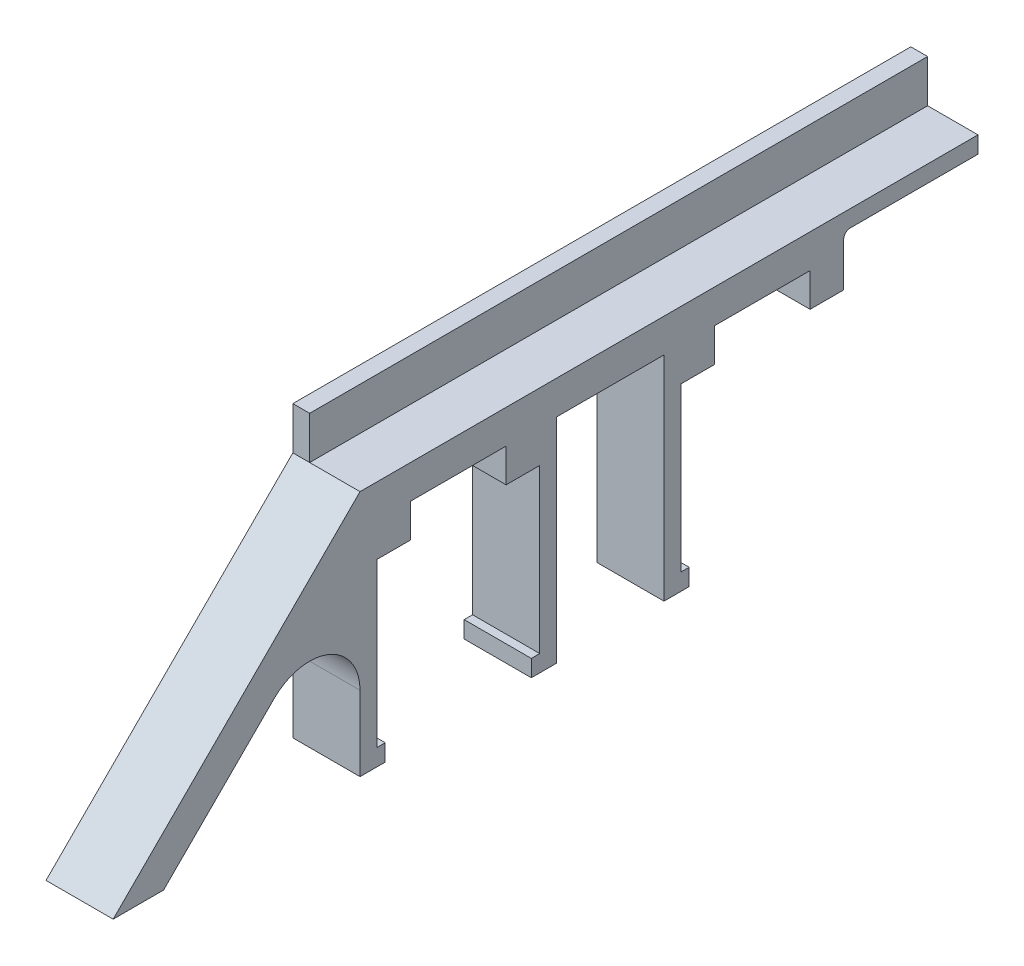
SolidWorks part; units mm, degrees
ref_plane "Front" through (0, 0, 0) normal (0, 0, 1) x (1, 0, 0)
ref_plane "Top" through (0, 0, 0) normal (0, 1, 0) x (1, 0, 0)
ref_plane "Right" through (0, 0, 0) normal (1, 0, 0) x (0, 0, -1)
sketch "Sketch1" plane through (0, 0, 0) normal (1, 0, 0) x (0, 0, -1)
  line L16 (-5, 68.5) -> (-5, -5)
  line L17 (-5, -5) -> (2.5, -5)
  line L18 (2.5, -5) -> (2.5, 0)
  line L19 (2.5, 0) -> (0, 0)
  line L20 (0, 0) -> (0, 48.5)
  line L21 (0, 48.5) -> (10, 48.5)
  line L22 (10, 48.5) -> (10, 58.5)
  line L23 (10, 58.5) -> (38.5, 58.5)
  line L24 (38.5, 58.5) -> (38.5, 48.5)
  line L25 (38.5, 48.5) -> (48.5, 48.5)
  line L26 (48.5, 48.5) -> (48.5, 0)
  line L27 (48.5, 0) -> (53.5, 0)
  line L28 (53.5, 0) -> (53.5, 58.5)
  line L29 (53.5, 58.5) -> (85.5, 58.5)
  line L30 (69.5, 58.5) -> (69.5, 90.1855)
  line L31 (-5, 68.5) -> (144, 68.5)
  line L32 (85.5, 0) -> (85.5, 58.5)
  line L33 (90.5, 0) -> (85.5, 0)
  line L34 (90.5, 48.5) -> (90.5, 0)
  line L35 (100.5, 48.5) -> (90.5, 48.5)
  line L36 (100.5, 58.5) -> (100.5, 48.5)
  line L37 (129, 58.5) -> (100.5, 58.5)
  line L38 (129, 48.5) -> (129, 58.5)
  line L39 (139, 48.5) -> (129, 48.5)
  line L40 (139, 0) -> (139, 48.5)
  line L41 (136.5, 0) -> (139, 0)
  line L42 (136.5, -5) -> (136.5, 0)
  line L43 (144, -5) -> (136.5, -5)
  line L44 (144, 68.5) -> (144, -5)
  line L45 (48.5, 0) -> (46, 0)
  line L46 (46, 0) -> (46, -5)
  line L47 (53.5, 0) -> (53.5, -5)
  line L48 (53.5, -5) -> (46, -5)
  line L49 (85.5, 0) -> (85.5, -5)
  line L50 (85.5, -5) -> (93, -5)
  line L51 (93, 0) -> (93, -5)
  line L52 (90.5, 0) -> (93, 0)
  line L53 (90.5, 0) -> (85.5, 0)
  line L54 (139, 48.5) -> (139, 68.5)
  line L55 (-5, 68.5) -> (-78.5, -5)
  line L56 (-5, -5) -> (-78.5, -5)
  line L57 (-78.5, -5) -> (-63.5, -5)
  line L58 (-63.5, -5) -> (-5, 53.5)
  line L59 (139, 63.5) -> (179, 63.5)
  line L60 (179, 63.5) -> (179, 68.5)
  line L61 (179, 68.5) -> (144, 68.5)
  point P9 (51, 0)
  point P32 (69.5, 68.5)
  dimension "D1" = 20
  dimension "D2" = 20
  dimension "D3" = 2.5
  dimension "D4" = 5
  dimension "D5" = 48.5
  dimension "D6" = 42
  dimension "D7" = 10
  dimension "D8" = 10
  dimension "D9" = 5
  dimension "D10" = 48.5
  dimension "D11" = 48.5
  dimension "D12" = 5
  dimension "D13" = 5
  dimension "D14" = 2.5
  dimension "D15" = 45
  dimension "D16" = 90
  dimension "D17" = 15
  dimension "D18" = 10
  dimension "D19" = 0
  dimension "D20" = 15
  dimension "D21" = 35
  dimension "D22" = 5
extrude "Boss-Extrude2" add sketch "Sketch1" along normal blind 20
fillet "Fillet1" radius 15 1 edges at (10, 53.5, 5)
fillet "Fillet2" radius 2 1 edges at (10, 63.5, -139)
sketch "Sketch2" plane through (0, 68.5, 0) normal (0, 1, 0) x (1, 0, 0)
  line L1 (5, 35) -> (5, 179)
  line L2 (20, 179) -> (0, 179) construction
  line L3 (0, -5) -> (0, 179) construction
  line L4 (20, -5) -> (0, -5) construction
  line L5 (0, -5) -> (0, 179)
  line L6 (0, 179) -> (5, 179)
  line L7 (5, 35) -> (5, -5)
  line L8 (5, -5) -> (0, -5)
  dimension "D1" = 5
  dimension "D2" = 40
extrude "Boss-Extrude3" add sketch "Sketch2" along normal blind 12.7
